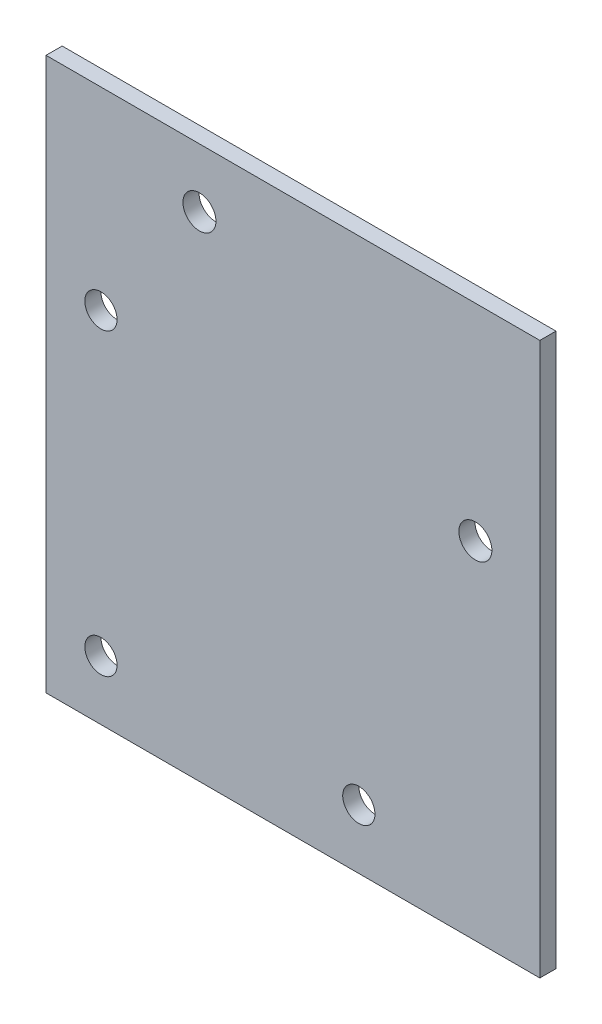
SolidWorks part; units mm, degrees
ref_plane "Front Plane" through (0, 0, 0) normal (0, 0, 1) x (1, 0, 0)
ref_plane "Top Plane" through (0, 0, 0) normal (0, 1, 0) x (1, 0, 0)
ref_plane "Right Plane" through (0, 0, 0) normal (1, 0, 0) x (0, 0, -1)
sketch "Sketch1" plane through (0, 0, 0) normal (0, 0, 1) x (1, 0, 0)
  line L0 (-18.7007, 195.3046) -> (-18.7007, 246.1046) construction
  line L1 (10.2553, 165.1875) -> (-87.0132, 165.1875)
  line L2 (10.2553, 165.1875) -> (10.2553, 273.9571)
  line L3 (10.2553, 273.9571) -> (-87.0132, 273.9571)
  line L4 (-87.0132, 165.1875) -> (-87.0132, 273.9571)
  line L5 (-18.7007, 246.1046) -> (-69.5007, 246.1046) construction
  circle A1 centre (-25.4, 176.8929) radius 3.175
  circle A2 centre (-76.2, 176.8929) radius 3.175
  circle A3 centre (-2.4447, 233.4046) radius 3.2512
  circle A4 centre (-56.8007, 262.3606) radius 3.2512
  circle A5 centre (-76.2, 235.8571) radius 3.175
  dimension "D2" = 6.35
  dimension "D3" = 6.35
  dimension "D1" = 6.35
  dimension "D12" = 6.5024
  dimension "D13" = 6.5024
  dimension "D4" = 10.8132
  dimension "D5" = 11.7054
  dimension "D6" = 38.1
  dimension "D7" = 16.256
  dimension "D8" = 12.7
  dimension "D9" = 12.7
  dimension "D10" = 16.256
  dimension "D11" = 12.7
extrude "Boss-Extrude1" add sketch "Sketch1" along normal blind 3.175
equation "\"80/20 to Center Hole\"= .64in"
equation "\"80/20 from Edge\"= 0.5in"
equation "\"D7@Sketch1\"=\"80/20 to Center Hole\""
equation "\"D8@Sketch1\"=\"80/20 from Edge\""
equation "\"D10@Sketch1\"=\"80/20 to Center Hole\""
equation "\"D11@Sketch1\"=\"80/20 from Edge\""
